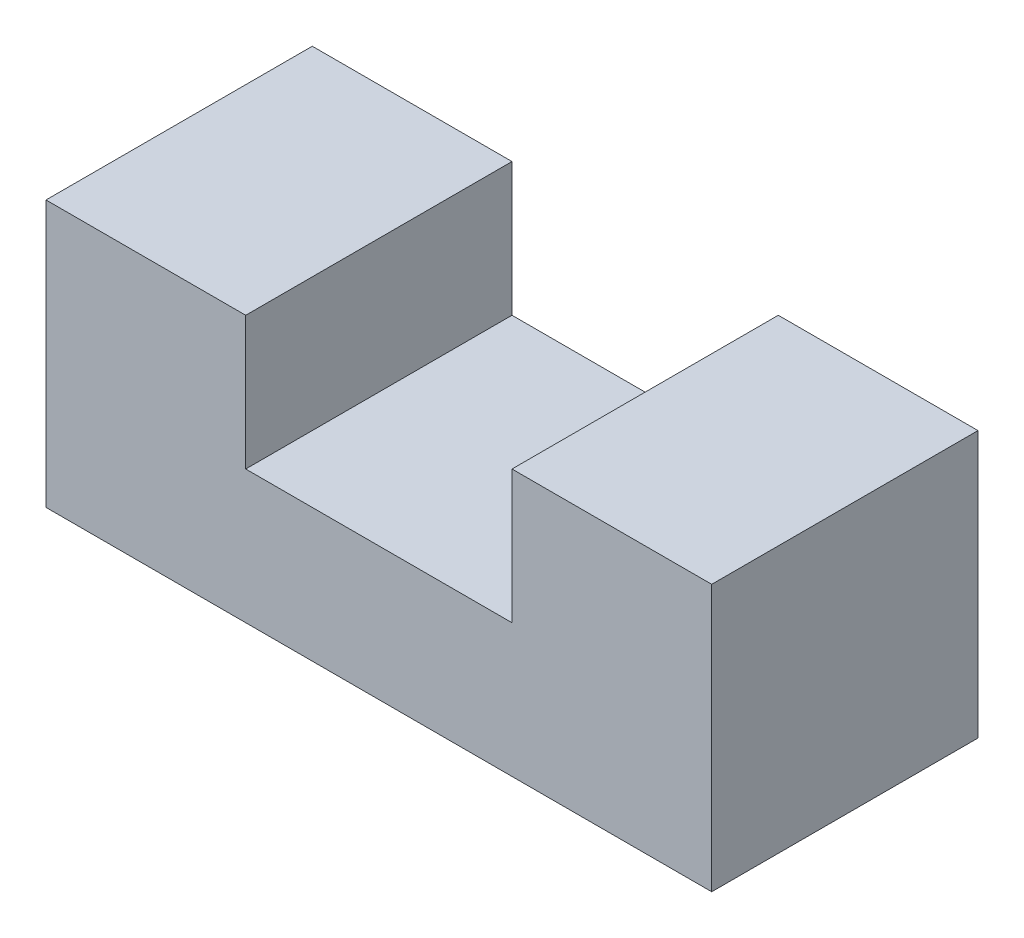
SolidWorks part; units mm, degrees
ref_plane "前基準面" through (0, 0, 0) normal (0, 0, 1) x (1, 0, 0)
ref_plane "上基準面" through (0, 0, 0) normal (0, 1, 0) x (1, 0, 0)
ref_plane "右基準面" through (0, 0, 0) normal (1, 0, 0) x (0, 0, -1)
sketch "草圖1" plane through (0, 0, 0) normal (0, 0, 1) x (1, 0, 0)
  line L1 (-25, 10) -> (25, 10)
  line L2 (-25, 10) -> (-25, -10)
  line L3 (-25, -10) -> (25, -10)
  line L4 (25, 10) -> (25, -10)
  line L5 (-25, 10) -> (25, -10) construction
  line L6 (-25, -10) -> (25, 10) construction
  line L7 (-10, 10) -> (10, 10)
  line L8 (-10, 10) -> (-10, 0)
  line L9 (-10, 0) -> (10, 0)
  line L10 (10, 10) -> (10, 0)
  point P0 (0, 0)
  dimension "D1" = 50
  dimension "D2" = 20
  dimension "D3" = 15
  dimension "D4" = 15
  dimension "D5" = 10
extrude "填料-伸長1" add sketch "草圖1" along normal blind 20 contours L1 L10 L9 L8 L2 L3 L4
